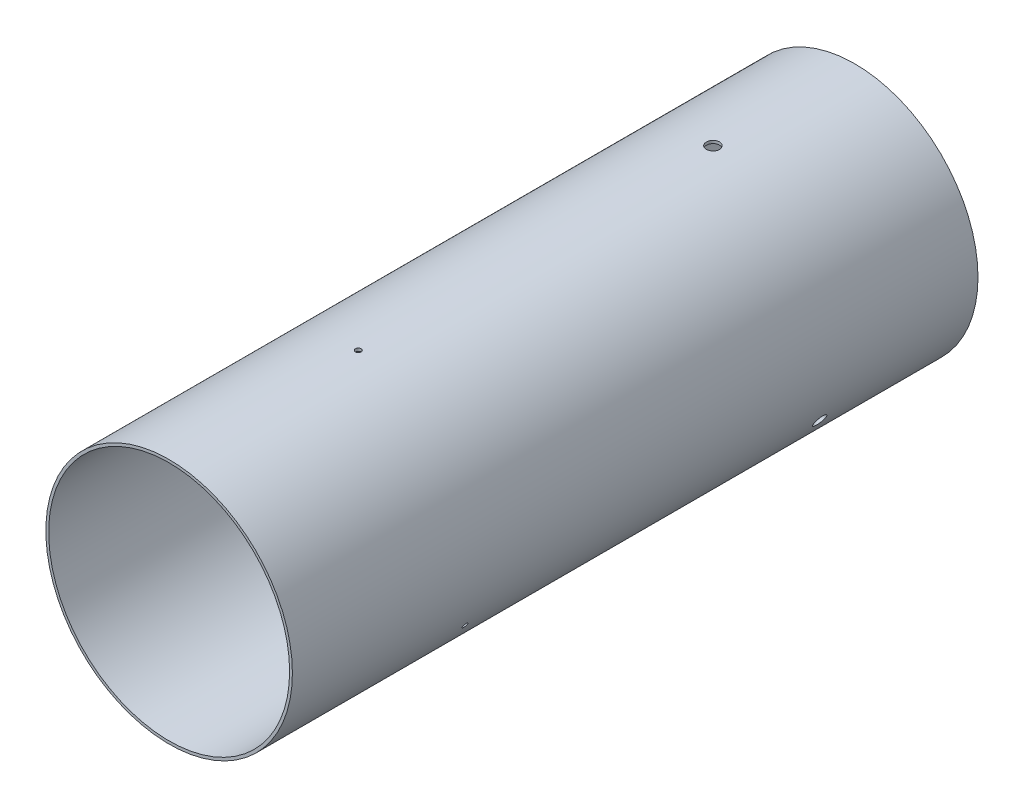
SolidWorks part; units mm, degrees
material "E-Glass Fiber"
ref_plane "Front Plane" through (0, 0, 0) normal (0, 0, 1) x (1, 0, 0)
ref_plane "Top Plane" through (0, 0, 0) normal (0, 1, 0) x (1, 0, 0)
ref_plane "Right Plane" through (0, 0, 0) normal (1, 0, 0) x (0, 0, -1)
sketch "Sketch1" plane through (0, 0, 0) normal (0, 0, 1) x (1, 0, 0)
  circle A0 centre (0, 0) radius 49.6697
  circle A1 centre (0, 0) radius 48.5394
  dimension "D1" = 99.3394
  dimension "D2" = 97.0788
extrude "Boss-Extrude1" add sketch "Sketch1" along normal blind 276.225
ref_plane "Plane1" through (0, 49.6697, 0) normal (0, 1, 0) x (1, 0, 0)
sketch "Sketch2" plane through (0, 49.6697, 0) normal (0, 1, 0) x (1, 0, 0)
  line L0 (0, 0) -> (0, -57.15) construction
  line L1 (0, -57.15) -> (0, 0) construction
  line L2 (-49.6697, -276.225) -> (49.6697, -276.225) construction
  line L3 (0, -57.15) -> (0, -200.025) construction
  line L4 (-48.5394, -276.225) -> (48.5394, -276.225) construction
  circle A0 centre (0, -57.15) radius 2.6289
  circle A2 centre (0, -200.025) radius 1.143
  dimension "D2" = 5.2578
  dimension "D6" = 2.286
  dimension "D1" = 57.15
  dimension "D3" = 276.225
  dimension "D5" = 76.2
extrude "8-32 T-Nut Holes" cut sketch "Sketch2" against normal blind 5.08
pattern_circular "CirPattern1" count 3 over 360 about axis through (0, 0, 276.225) along (0, 0, -1) of "8-32 T-Nut Holes"
